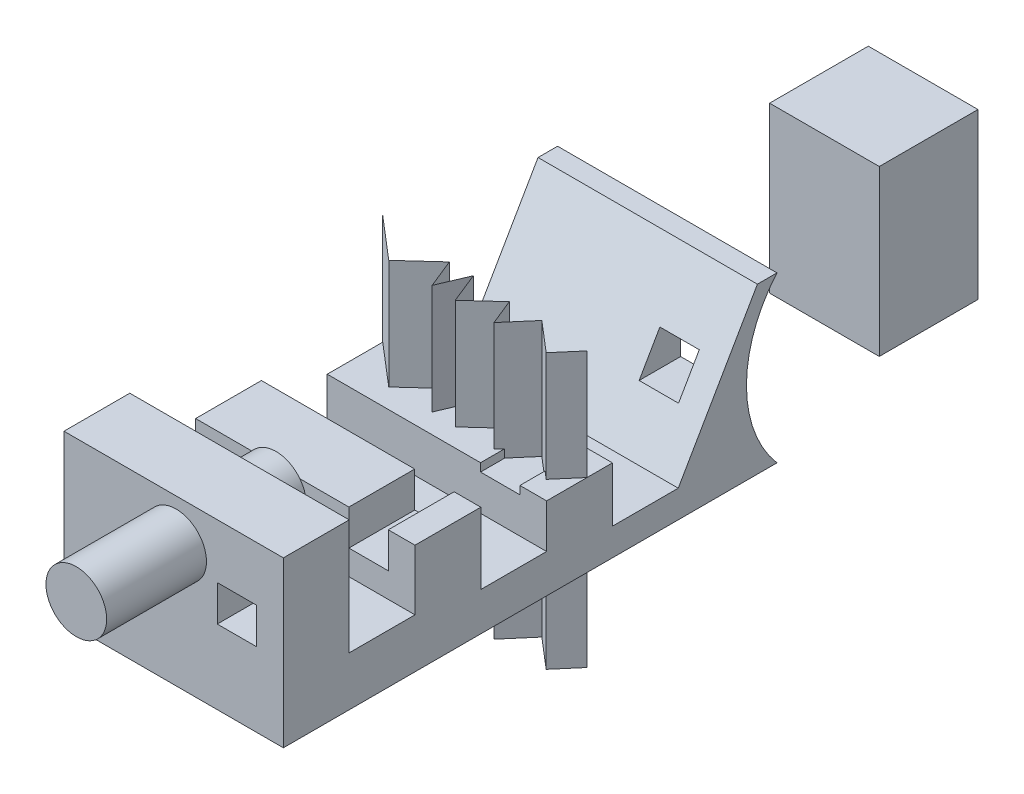
SolidWorks part; units mm, degrees
material "AISI 1020"
ref_plane "Front Plane" through (0, 0, 0) normal (0, 0, 1) x (1, 0, 0)
ref_plane "Top Plane" through (0, 0, 0) normal (0, 1, 0) x (1, 0, 0)
ref_plane "Right Plane" through (0, 0, 0) normal (1, 0, 0) x (0, 0, -1)
sketch "Sketch1" plane through (0, 0, 0) normal (1, 0, 0) x (0, 0, -1)
  line L0 (0, 0) -> (0, 150)
  line L1 (0, 150) -> (60, 150)
  line L2 (60, 150) -> (60, 45)
  line L3 (60, 45) -> (120, 45)
  line L4 (120, 45) -> (120, 100)
  line L5 (120, 100) -> (180, 100)
  line L6 (180, 100) -> (180, 35)
  line L7 (180, 35) -> (240, 35)
  line L8 (240, 35) -> (240, 75)
  line L9 (240, 75) -> (300, 75)
  line L10 (300, 75) -> (300, 25)
  line L11 (300, 25) -> (360, 25)
  line L12 (360, 25) -> (432.1688, 150)
  line L13 (432.1688, 150) -> (450, 150)
  line L14 (450, 150) -> (450, 0) construction
  line L15 (450, 0) -> (0, 0)
  arc A0 (450, 150) -> (450, 0) centre (537.178, 75) ccw
  dimension "D1" = 150
  dimension "D6" = 115
  dimension "D2" = 450
  dimension "D3" = 45
  dimension "D4" = 35
  dimension "D5" = 25
  dimension "D7" = 60
  dimension "D8" = 60
  dimension "D9" = 100
  dimension "D10" = 75
extrude "Boss-Extrude1" add sketch "Sketch1" along normal mid plane 200
sketch "Sketch2" plane through (0, 0, 0) normal (0, -1, 0) x (1, 0, 0)
  line L1 (-37.3512, -580.6298) -> (62.6488, -580.6298)
  line L2 (-37.3512, -580.6298) -> (-37.3512, -670.6298)
  line L3 (-37.3512, -670.6298) -> (62.6488, -670.6298)
  line L4 (62.6488, -580.6298) -> (62.6488, -670.6298)
  dimension "D2" = 90
  dimension "D3" = 100
extrude "Boss-Extrude2" add sketch "Sketch2" against normal blind 150 separate body
sketch "Sketch3" plane through (0, 75, 0) normal (0, 1, 0) x (1, 0, 0)
  line L0 (-100, 290.5855) -> (-61.8619, 257.9496)
  line L1 (-100, 300) -> (-100, 240) construction
  line L2 (-61.8619, 257.9496) -> (-32.9918, 284.3093)
  line L3 (-32.9918, 284.3093) -> (-22.3224, 257.9496)
  line L4 (-22.3224, 257.9496) -> (-11.153, 284.3093)
  line L5 (-11.153, 284.3093) -> (0, 256.7548)
  line L6 (0, 256.7548) -> (25.744, 280.2602)
  line L7 (25.744, 280.2602) -> (35.2581, 256.7548)
  line L8 (35.2581, 256.7548) -> (55.3724, 280.2602)
  line L9 (55.3724, 280.2602) -> (82.8407, 256.7548)
  line L10 (82.8407, 256.7548) -> (100, 276.807)
  line L11 (100, 300) -> (100, 240) construction
surface "Surface-Extrude1" sketch "Sketch3" parameters "D1"=100, "D2"=150
sketch "Sketch4" plane through (0, 0, 0) normal (0, 0, 1) x (1, 0, 0)
  circle A0 centre (2.2172, 112.008) radius 27.6674
extrude "Boss-Extrude3" add sketch "Sketch4" against normal mid plane 182
sketch "Sketch5" plane through (0, 0, 0) normal (0, 0, 1) x (1, 0, 0)
  line L1 (39.7488, 100.3833) -> (75.6621, 100.3833)
  line L2 (39.7488, 100.3833) -> (39.7488, 67.608)
  line L3 (39.7488, 67.608) -> (75.6621, 67.608)
  line L4 (75.6621, 100.3833) -> (75.6621, 67.608)
extrude "Cut-Extrude1" cut sketch "Sketch5" against normal up to surface (425.0143 mm away)
